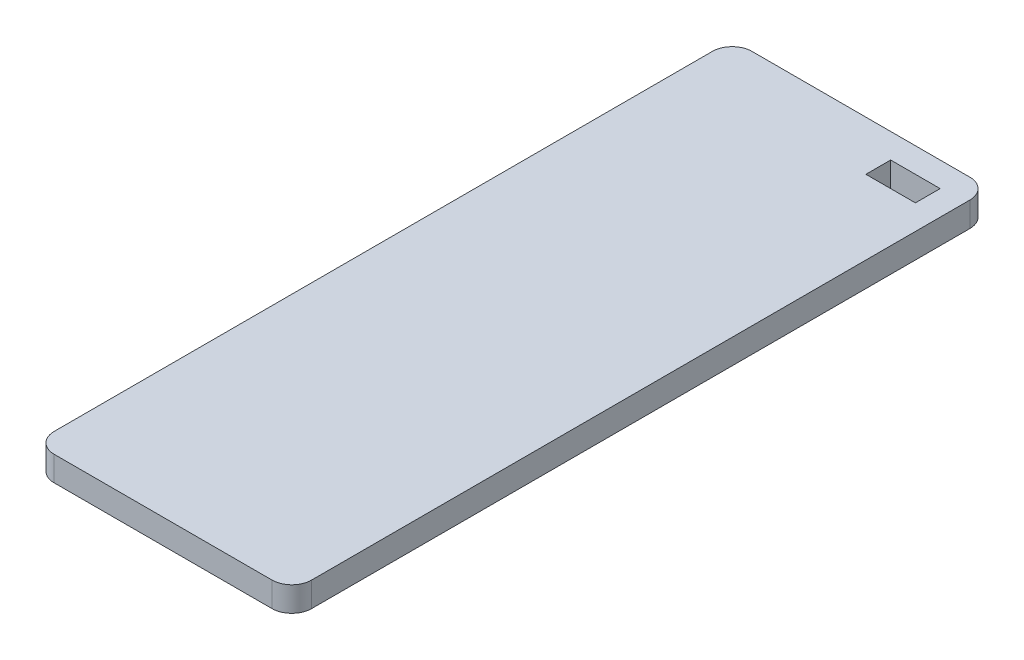
SolidWorks part; units mm, degrees
material "Acrylic (Medium-high impact)"
ref_plane "Front Plane" through (0, 0, 0) normal (0, 0, 1) x (1, 0, 0)
ref_plane "Top Plane" through (0, 0, 0) normal (0, 1, 0) x (1, 0, 0)
ref_plane "Right Plane" through (0, 0, 0) normal (1, 0, 0) x (0, 0, -1)
ref_plane "Plane1" through (0, 0, 0) normal (0, 1, 0) x (1, 0, 0)
sketch "Sketch1" plane through (0, 0, 0) normal (0, 1, 0) x (1, 0, 0)
  line L1 (-26.2811, -33.3088) -> (6.7489, -33.3088)
  line L2 (-26.2811, -33.3088) -> (-26.2811, 56.2162)
  line L3 (-26.2811, 56.2162) -> (6.7489, 56.2162)
  line L4 (6.7489, -33.3088) -> (6.7489, 56.2162)
  dimension "D1" = 89.525
  dimension "D2" = 33.03
extrude "Boss-Extrude1" add sketch "Sketch1" along normal blind 3.175
sketch "Sketch2" plane through (0, 3.175, 0) normal (0, 1, 0) x (1, 0, 0)
  line L1 (-2.7761, 49.8662) -> (3.5739, 49.8662)
  line L2 (-2.7761, 49.8662) -> (-2.7761, 53.0412)
  line L3 (-2.7761, 53.0412) -> (3.5739, 53.0412)
  line L4 (3.5739, 49.8662) -> (3.5739, 53.0412)
  line L6 (6.7489, 56.2162) -> (-26.2811, 56.2162) construction
  line L7 (6.7489, -33.3088) -> (6.7489, 56.2162) construction
  dimension "D1" = 3.175
  dimension "D2" = 3.175
  dimension "D3" = 6.35
  dimension "D4" = 3.175
extrude "Cut-Extrude1" cut sketch "Sketch2" against normal through all
fillet "Fillet1" radius 2.54 4 edges at (-26.2811, 1.5875, -56.2162) (6.7489, 1.5875, -56.2162) (6.7489, 1.5875, 33.3088) (-26.2811, 1.5875, 33.3088)
